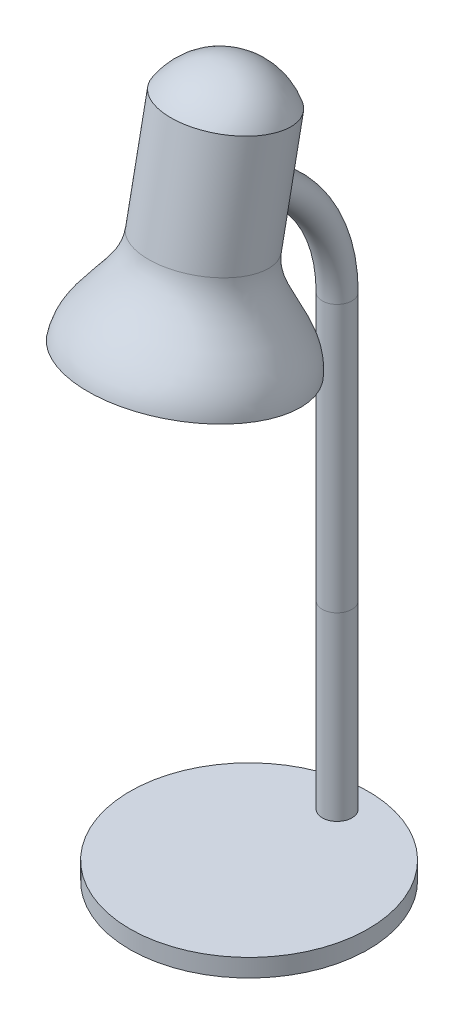
SolidWorks part; units mm, degrees
ref_plane "前视基准面" through (0, 0, 0) normal (0, 0, 1) x (1, 0, 0)
ref_plane "上视基准面" through (0, 0, 0) normal (0, 1, 0) x (1, 0, 0)
ref_plane "右视基准面" through (0, 0, 0) normal (1, 0, 0) x (0, 0, -1)
sketch "草图2" plane through (0, 0, 0) normal (0, 1, 0) x (1, 0, 0)
  circle A0 centre (0, 0) radius 100
  dimension "D1" = 200
extrude "凸台-拉伸1" add sketch "草图2" along normal blind 15
sketch "草图3" plane through (0, 0, 0) normal (1, 0, 0) x (0, 0, -1)
  line L0 (73.9028, 15) -> (73.9028, 166.5627)
  line L1 (100, 15) -> (-100, 15) construction
  line L2 (73.9028, 166.5627) -> (73.9028, 390.71)
  arc A0 (73.9028, 390.71) -> (-31.4666, 519.2104) centre (-57.1366, 390.71) ccw
sketch "草图4" plane through (0, 15, 0) normal (0, 1, 0) x (1, 0, 0)
  line L0 (0, -31.4666) -> (0, 73.9028) construction
  circle A0 centre (0, 73.9028) radius 12.5
  dimension "D1" = 25
sweep "扫描1" add profiles "草图4" path "草图3"
sketch "草图6" plane through (0, 25.9694, 129.9993) normal (0, 0.1959, 0.9806) x (1, 0, 0)
  line L0 (0, 388.4987) -> (0, 591.5988)
  line L1 (46.8286, 563.0324) -> (46.8286, 467.5789)
  line L2 (83.0592, 388.4987) -> (0, 388.4987)
  arc A1 (0, 591.5988) -> (46.8286, 563.0324) centre (0, 538.9328) cw
  spline S0 degree 3 poles (46.8286, 467.5789) (47.0769, 435.3107) (81.2297, 420.2267) (83.0592, 388.4987) knots 0 0 0 0 1 1 1 1
revolve "旋转1" add sketch "草图6" angle 360 about L0
